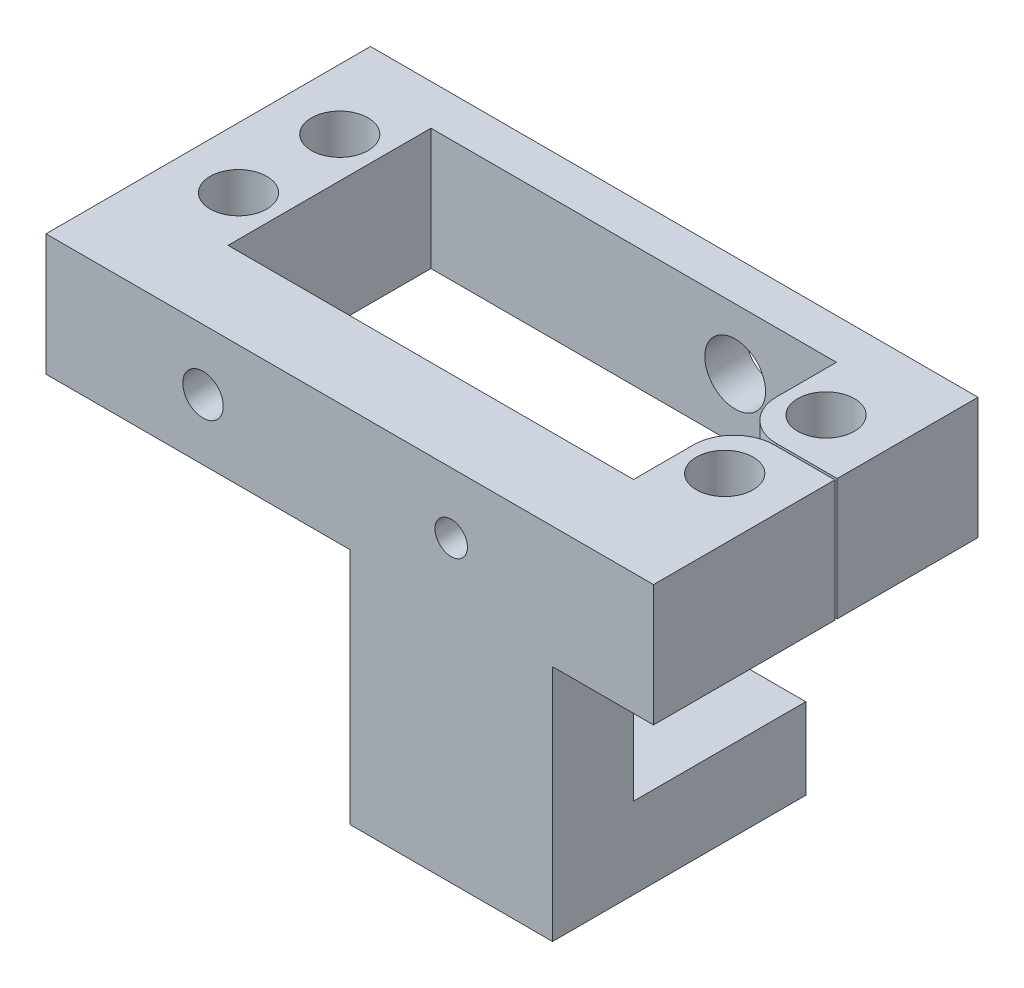
SolidWorks part; units mm, degrees
ref_plane "Front Plane" through (0, 0, 0) normal (0, 0, 1) x (1, 0, 0)
ref_plane "Top Plane" through (0, 0, 0) normal (0, 1, 0) x (1, 0, 0)
ref_plane "Right Plane" through (0, 0, 0) normal (1, 0, 0) x (0, 0, -1)
sketch "Sketch1" plane through (0, 0, 0) normal (0, 1, 0) x (1, 0, 0)
  line L0 (20.015, 0) -> (27.985, 0)
  line L1 (27.985, -14.015) -> (-27.985, -14.015)
  line L2 (27.985, -14.015) -> (27.985, 14.015)
  line L3 (27.985, 14.015) -> (-27.985, 14.015)
  line L4 (-27.985, -14.015) -> (-27.985, 14.015)
  line L5 (27.985, -14.015) -> (-27.985, 14.015) construction
  line L6 (27.985, 14.015) -> (-27.985, -14.015) construction
  line L7 (20.015, -10.015) -> (-20.015, -10.015)
  line L8 (20.015, -10.015) -> (20.015, 10.015)
  line L9 (20.015, 10.015) -> (-20.015, 10.015)
  line L10 (-20.015, -10.015) -> (-20.015, 10.015)
  line L11 (20.015, -10.015) -> (-20.015, 10.015) construction
  line L12 (20.015, 10.015) -> (-20.015, -10.015) construction
  line L13 (24, -5) -> (-24, -5) construction
  line L14 (24, -5) -> (24, 5) construction
  line L15 (24, 5) -> (-24, 5) construction
  line L16 (-24, -5) -> (-24, 5) construction
  line L17 (24, -5) -> (-24, 5) construction
  line L18 (24, 5) -> (-24, -5) construction
  line L19 (-27.985, -14.015) -> (-27.985, -18.015)
  line L20 (-27.985, -18.015) -> (27.985, -18.015)
  line L21 (27.985, -18.015) -> (27.985, -14.015)
  line L22 (27.985, 14.015) -> (29.985, 14.015)
  line L23 (29.985, 14.015) -> (29.985, 0.115)
  line L24 (29.985, 0.115) -> (24, 0.115)
  line L25 (27.985, -14.015) -> (29.985, -14.015)
  line L26 (29.985, -14.015) -> (29.985, -0.115)
  line L27 (29.985, -0.115) -> (24, -0.115)
  line L28 (27.985, -18.015) -> (29.985, -18.015)
  line L29 (29.985, -18.015) -> (29.985, -14.015)
  line L30 (-27.985, 14.015) -> (-29.985, 14.015)
  line L31 (-29.985, 14.015) -> (-29.985, -18.015)
  line L32 (-29.985, -18.015) -> (-27.985, -18.015)
  line L33 (-20.015, -18.015) -> (-20.015, -74.515)
  line L34 (-20.015, -74.515) -> (17.515, -74.515)
  line L35 (17.515, -74.515) -> (17.515, -84.485)
  line L36 (17.515, -84.485) -> (-29.985, -84.485)
  line L37 (-29.985, -84.485) -> (-29.985, -18.015)
  line L38 (-20.015, -74.515) -> (-29.985, -74.515) construction
  circle A1 centre (24, 5) radius 2.8
  circle A2 centre (24, -5) radius 2.8
  circle A3 centre (-24, -5) radius 2.8
  circle A4 centre (-24, 5) radius 2.8
  arc A5 (20.015, 4.1) -> (27.985, 4.1) centre (24, 4.1) ccw
  arc A6 (20.015, -4.1) -> (27.985, -4.1) centre (24, -4.1) cw
  point P0 (0, 0)
  point P6 (0, 0)
  point P11 (0, 0)
  dimension "D1" = 5.6
  dimension "D7" = 4.1
  dimension "D8" = 4.1
  dimension "D2" = 48
  dimension "D3" = 4
  dimension "D4" = 40.03
  dimension "D5" = 20.03
  dimension "D6" = 10
  dimension "D9" = 4
  dimension "D10" = 2
  dimension "D11" = 2
  dimension "D12" = 56.5
  dimension "D13" = 47.5
extrude "Boss-Extrude1" add sketch "Sketch1" along normal mid plane 12 contours A6 L8 L7 L10 L9 A5 L2 L3 L4 L1 A4 A3 A2 A1 | L20 L21 L1 L19 | L24 L23 L22 L2 | L26 L27 L2 L25 | L27 A6 L2 | A5 L24 L2 | L28 L29 L25 L21 | L31 L32 L19 L4 L30
sketch "Sketch2" plane through (0, -6, 0) normal (0, -1, 0) x (1, 0, 0)
  circle A0 centre (24, -5) radius 2.8 construction
  circle A1 centre (24, 5) radius 2.8 construction
  circle A2 centre (-24, -5) radius 2.8 construction
  circle A3 centre (-24, 5) radius 2.8 construction
  circle A4 centre (24, -5) radius 2.8
  circle A5 centre (24, 5) radius 2.8
  circle A6 centre (-24, -5) radius 2.8
  circle A7 centre (-24, 5) radius 2.8
extrude "Boss-Extrude2" add sketch "Sketch2" against normal offset from surface (3.5 mm away) 8.5 up to face at (10.4535, 6, 0.5714)
sketch "Sketch3" plane through (0, 0, 18.015) normal (0, 0, 1) x (1, 0, 0)
  line L0 (10.015, 0) -> (-10.485, 0) construction
  line L1 (-10.485, 0) -> (-14.485, 0) construction
  circle A2 centre (10.015, 0) radius 1.6
  circle A3 centre (-14.485, 0) radius 1.6
  dimension "D3" = 3.2
  dimension "D4" = 3.2
  dimension "D1" = 4
  dimension "D2" = 20.5
  dimension "D5" = 10
extrude "Cut-Extrude1" cut sketch "Sketch3" against normal blind 10 contours A2
sketch "Sketch4" plane through (0, 0, -14.015) normal (0, 0, -1) x (-1, 0, 0)
  line L4 (-29.985, -6) -> (29.985, -6)
  line L5 (29.985, -6) -> (29.985, 6)
  line L6 (29.985, 6) -> (-29.985, 6)
  line L7 (-29.985, 6) -> (-29.985, -6)
  line L8 (-29.985, -6) -> (29.985, -6)
  line L10 (29.985, 6) -> (-29.985, 6)
  line L12 (-29.985, 6) -> (-29.985, -6)
  line L13 (29.985, -6) -> (29.985, 6)
  circle A2 centre (-10.015, 0) radius 3
  circle A6 centre (-10.015, 0) radius 1.6 construction
  circle A7 centre (-10.015, 0) radius 1.6 construction
  dimension "D2" = 6
  dimension "D1" = 0
extrude "Cut-Extrude2" cut sketch "Sketch4" against normal offset from surface (28.03 mm away) 4 contours A2 up to face at (11.615, 0, 18.015)
sketch "Sketch5" plane through (0, 0, 0) normal (1, 0, 0) x (0, 0, -1)
  line L0 (-18.015, -6) -> (-10.015, -6)
  line L1 (-10.015, -6) -> (-10.015, -21.5)
  line L2 (-10.015, -21.5) -> (6.985, -21.5)
  line L3 (6.985, -21.5) -> (6.985, -29.5)
  line L4 (6.985, -29.5) -> (-18.015, -29.5)
  line L5 (-18.015, -29.5) -> (-18.015, -6)
  line L7 (14.015, 6) -> (0.115, 6) construction
  dimension "D1" = 27.5
  dimension "D2" = 8
  dimension "D3" = 25
extrude "Boss-Extrude3" add sketch "Sketch5" along normal up to surface (20.015 mm away) up to face at (20.015, 0, 7.0575)
sketch "Sketch6" plane through (0, -29.5, 0) normal (0, -1, 0) x (1, 0, 0)
  line L0 (0, 0) -> (10.015, 0) construction
  line L1 (20.015, -4.1) -> (20.015, -10.015) construction
  circle A0 centre (10.015, 0) radius 2
  dimension "D2" = 4
  dimension "D1" = 10
extrude "Cut-Extrude3" cut sketch "Sketch6" against normal blind 6
sketch "Sketch10" plane through (0, 0, 18.015) normal (0, 0, 1) x (1, 0, 0)
  circle A0 centre (-14.485, 0) radius 2
  dimension "D1" = 4
extrude "Cut-Extrude6" cut sketch "Sketch10" against normal blind 8 and the other way through all
